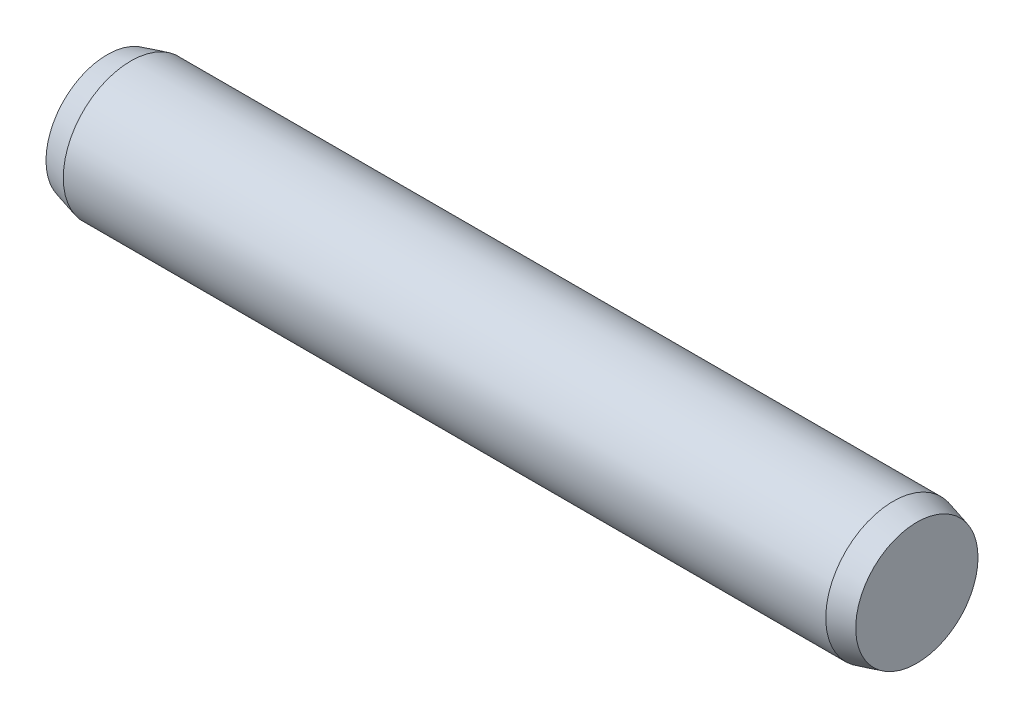
SolidWorks part; units mm, degrees
material "Chrome Stainless Steel"
ref_plane "Front Plane" through (0, 0, 0) normal (0, 0, 1) x (1, 0, 0)
ref_plane "Top Plane" through (0, 0, 0) normal (0, 1, 0) x (1, 0, 0)
ref_plane "Right Plane" through (0, 0, 0) normal (1, 0, 0) x (0, 0, -1)
sketch "Sketch1" plane through (0, 0, 0) normal (0, 0, 1) x (1, 0, 0)
  line L0 (-5.65, 0) -> (5.65, 0) construction
  line L1 (5.65, 1) -> (5.65, -1) construction
  line L2 (-5.65, 1) -> (-5.65, -1) construction
  line L3 (6, 1) -> (6, -1) construction
  line L4 (-6, 1) -> (-6, -1) construction
  line L5 (-5.65, 0) -> (-6, 0) construction
  line L6 (5.65, 0) -> (6, 0) construction
  point P11 (4, 0)
  point P21 (-4, 0)
  dimension "Diameter" = 2
  dimension "Chamfer" = 0.35
  dimension "D1" = 0.35
  dimension "Length" = 12
  dimension "D2" = 2
  dimension "D3" = 2
sketch "Sketch2" plane through (0, 0, 0) normal (1, 0, 0) x (0, 0, -1)
  circle A0 centre (0, 0) radius 1
extrude "Extrude1" add sketch "Sketch2" against normal up to vertex (5.65 mm away) and the other way up to vertex (5.65 mm away) up to point (-5.65, 1, 0) other way up to point (5.65, 1, 0)
sketch "Sketch3" plane through (5.65, 0, 0) normal (1, 0, 0) x (0, 0, -1)
  circle A1 centre (0, 0) radius 1
  circle A2 centre (0, 0) radius 1
  dimension "D1" = 0
extrude "Extrude2" add sketch "Sketch3" along normal up to vertex (0.35 mm away) draft 15 up to point (6, 0, 0)
sketch "Sketch4" plane through (-5.65, 0, 0) normal (-1, 0, 0) x (0, 0, 1)
  circle A1 centre (0, 0) radius 1
  circle A2 centre (0, 0) radius 1
  dimension "D1" = 0
extrude "Extrude3" add sketch "Sketch4" along normal up to vertex (0.35 mm away) draft 15 up to point (-6, 0, 0)
sketch "Sketch5" plane through (0, 0, 0) normal (1, 0, 0) x (0, 0, -1)
  line L0 (-1, 0) -> (1, 0) construction
  point P4 (0, 0)
  dimension "D1" = 2
equation "\"D1@Sketch1\" = \"Chamfer@Sketch1\""
equation "\"D1@Sketch5\" = \"Diameter@Sketch1\""
equation "\"D2@Sketch1\" = \"Diameter@Sketch1\""
equation "\"D3@Sketch1\"=\"D2@Sketch1\""
